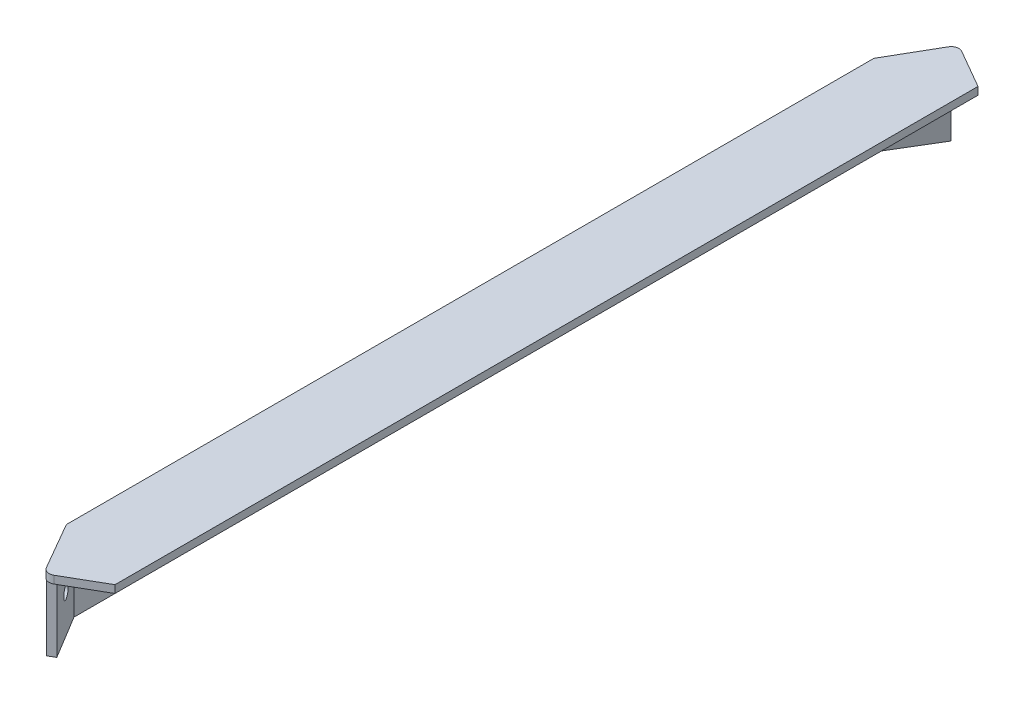
SolidWorks part; units mm, degrees
material "1.0116 (S235J2G3)"
ref_plane "Front Plane" through (0, 0, 0) normal (0, 0, 1) x (1, 0, 0)
ref_plane "Top Plane" through (0, 0, 0) normal (0, 1, 0) x (1, 0, 0)
ref_plane "Right Plane" through (0, 0, 0) normal (1, 0, 0) x (0, 0, -1)
sketch "Sketch1" plane through (0, 0, 0) normal (0, 0, 1) x (1, 0, 0)
  line L6 (0, 0) -> (0, 70)
  line L7 (0, 70) -> (70, 70)
  line L8 (70, 70) -> (70, 63)
  line L9 (70, 63) -> (7, 63)
  line L10 (7, 63) -> (7, 0)
  line L11 (7, 0) -> (0, 0)
  dimension "D1" = 70
  dimension "D2" = 70
  dimension "D3" = 7
  dimension "D4" = 7
extrude "Boss-Extrude1" add sketch "Sketch1" along normal blind 370
sketch "Sketch2" plane through (0, 0, 0) normal (0, 1, 0) x (1, 0, 0)
  line L0 (0, -370) -> (25, -413.3013)
  line L1 (25, -413.3013) -> (31.0622, -409.8013)
  line L2 (31.0622, -409.8013) -> (7, -370)
  line L3 (0, -370) -> (7, -370) construction
  line L4 (7, -370) -> (0, -370)
  line L5 (0, -370) -> (0, 0) construction
  dimension "D1" = 46.5095
  dimension "D2" = 50
  dimension "D3" = 210
  dimension "D4" = 7
extrude "Boss-Extrude2" add sketch "Sketch2" along normal blind 63
sketch "Sketch9" plane through (0, 63, 0) normal (0, 1, 0) x (1, 0, 0)
  line L0 (0, -370) -> (25, -413.3013)
  line L1 (34.5622, -415.8634) -> (70, -395.4034)
  line L2 (70, -395.4034) -> (70, -370)
  line L3 (70, -370) -> (0, -370)
  arc A0 (25, -413.3013) -> (34.5622, -415.8634) centre (31.0622, -409.8013) ccw
  dimension "D5" = 14
  dimension "D2" = 40.9201
  dimension "D1" = 90
  dimension "D3" = 90
  dimension "D4" = 60
  dimension "D6" = 7
  dimension "D7" = 7
extrude "Boss-Extrude4" add sketch "Sketch9" along normal blind 7
sketch "Sketch10" plane through (-158.6877, 0, 95.9359) normal (0.8558, 0, -0.5174) x (-0.5174, 0, -0.8558)
  line L0 (-366.7649, 63) -> (-366.7649, 0) construction
  line L1 (-366.7649, 0) -> (-320.2554, 0) construction
  circle A0 centre (-341.7649, 35) radius 6
  dimension "D1" = 12
  dimension "D2" = 25
  dimension "D3" = 35
extrude "Cut-Extrude3" cut sketch "Sketch10" against normal blind 7
sketch "Sketch21" plane through (0, 0, 0) normal (0, 0, -1) x (-1, 0, 0)
  line L0 (0, 70) -> (-70, 70) construction
  line L1 (-70, 70) -> (-70, 0) construction
  line L2 (-70, 0) -> (0, 0) construction
  line L3 (0, 0) -> (0, 69.2595) construction
fillet "Fillet5" radius 5 2 edges at (19.0311, 63, 389.9006) (7, 63, 185)
mirror "Mirror6" about plane through (0, 0, 0) normal (0, 0, 1) of bodies 107 108
